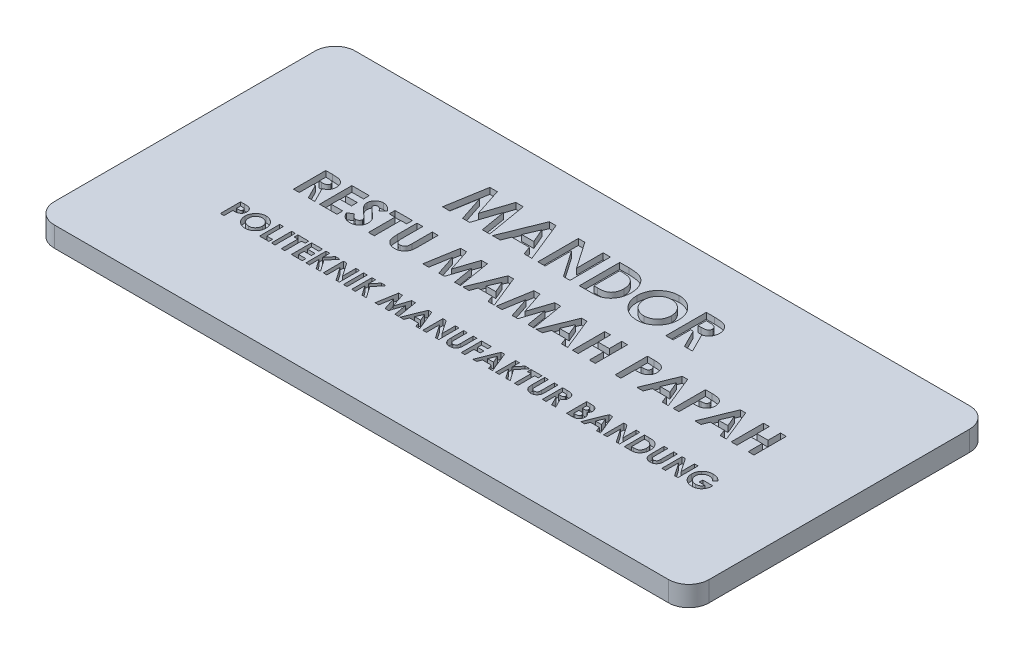
SolidWorks part; units mm, degrees
ref_plane "Front Plane" through (0, 0, 0) normal (0, 0, 1) x (1, 0, 0)
ref_plane "Top Plane" through (0, 0, 0) normal (0, 1, 0) x (1, 0, 0)
ref_plane "Right Plane" through (0, 0, 0) normal (1, 0, 0) x (0, 0, -1)
sketch "Sketch4" plane through (0, 0, 0) normal (0, 1, 0) x (1, 0, 0)
  line L1 (-81, -37.25) -> (81, -37.25)
  line L2 (-81, -37.25) -> (-81, 37.25)
  line L3 (-81, 37.25) -> (81, 37.25)
  line L4 (81, -37.25) -> (81, 37.25)
  line L5 (-81, -37.25) -> (81, 37.25) construction
  line L6 (-81, 37.25) -> (81, -37.25) construction
  point P0 (0, 0)
  dimension "D1" = 162
  dimension "D2" = 74.5
extrude "Boss-Extrude1" add sketch "Sketch4" along normal blind 5
fillet "Fillet1" radius 5 4 edges at (81, 2.5, 37.25) (81, 2.5, -37.25) (-81, 2.5, 37.25) (-81, 2.5, -37.25)
sketch "Sketch6" plane through (0, 5, 0) normal (0, 1, 0) x (1, 0, 0)
  line L0 (-32.9379, 14.6723) -> (32.9379, 14.6723) construction
  line L1 (-72.9373, -14.2505) -> (77.0627, -14.2505) construction
  line L2 (-55, 0) -> (55, 0) construction
  line L4 (-2.75, 0) -> (2.75, 0) construction
  text T0 "<b>MANDOR</b>" font "Century Gothic" height 10
  text T1 "<b>RESTU MAMAH PAPAH</b>" font "Century Gothic" height 8
  text T2 "<b>POLITEKNIK MANUFAKTUR BANDUNG</b>" font "Century Gothic" height 5
  point P3 (0, 14.6723)
  point P7 (0, 0)
  point P13 (2.0627, -14.2505)
  dimension "D1" = 110
  dimension "D2" = 150
extrude "Cut-Extrude1" cut sketch "Sketch6" against normal blind 1.5
